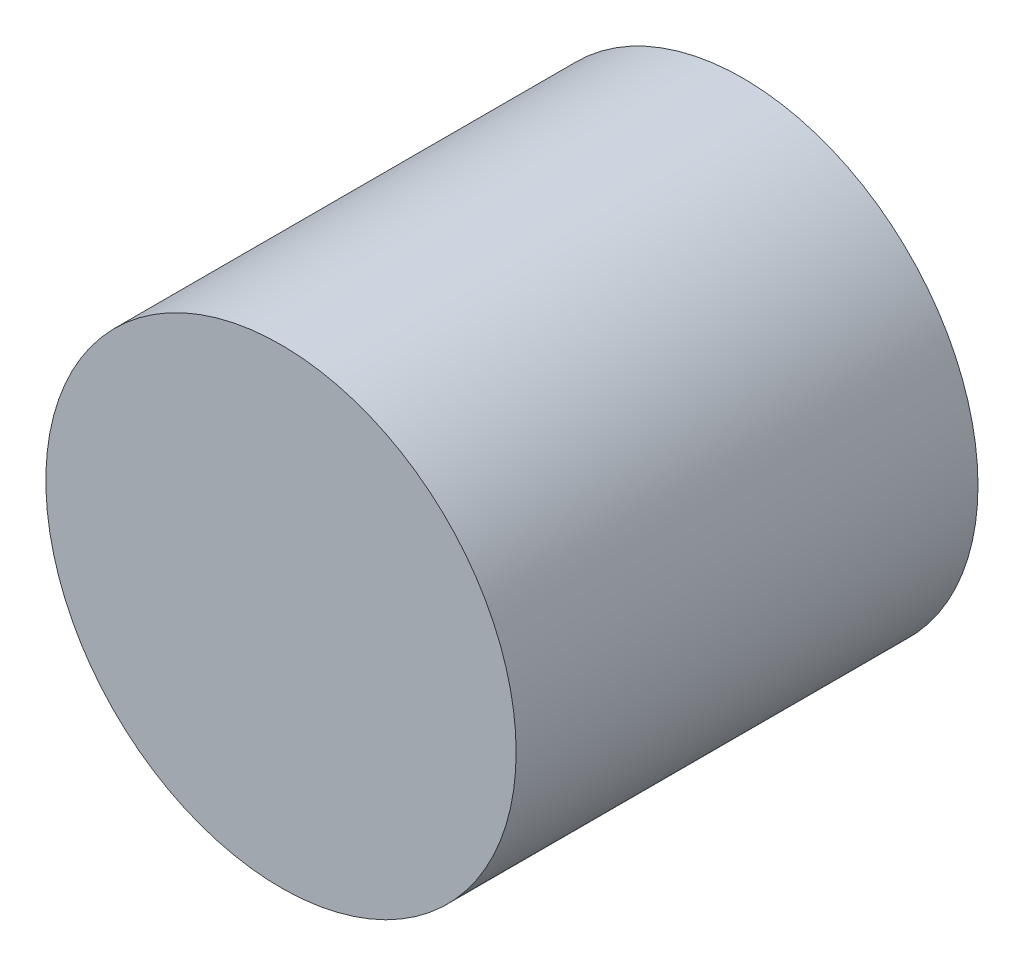
SolidWorks part; units mm, degrees
ref_plane "Plan1" through (0, 0, 0) normal (0, 0, 1) x (1, 0, 0)
ref_plane "Plan2" through (0, 0, 0) normal (0, 1, 0) x (1, 0, 0)
ref_plane "Plan3" through (0, 0, 0) normal (1, 0, 0) x (0, 0, -1)
sketch "Esquisse1" plane through (0, 0, 0) normal (0, 0, 1) x (1, 0, 0)
  circle A0 centre (0, 0) radius 5.0915
  dimension "D1" = 10.183
extrude "Base-Extrusion" add sketch "Esquisse1" against normal blind 10
